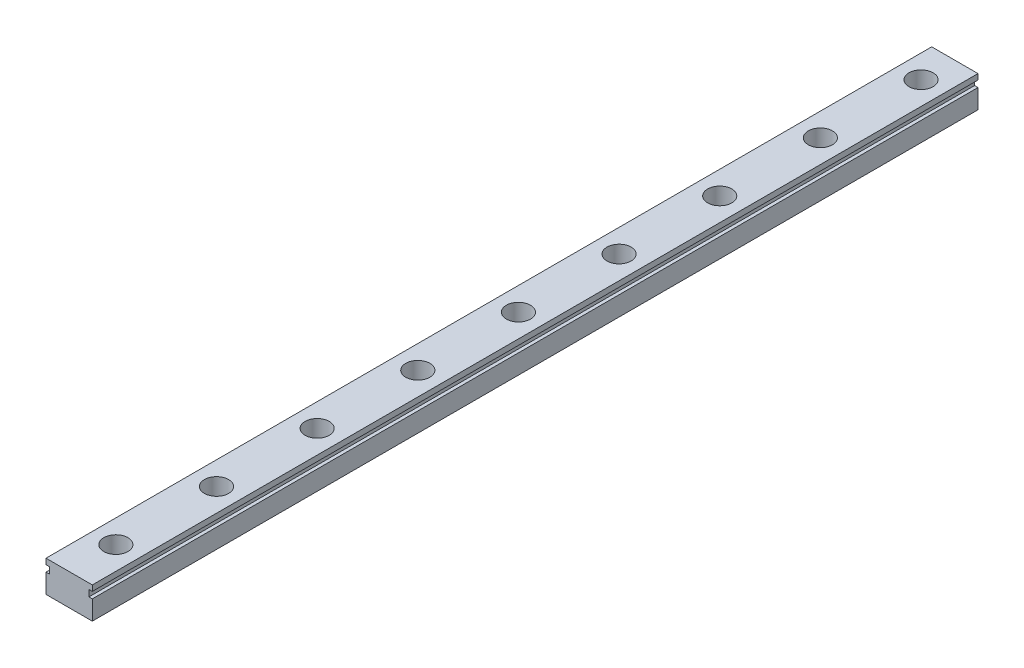
SolidWorks part; units mm, degrees
ref_plane "Front Plane" through (0, 0, 0) normal (0, 0, 1) x (1, 0, 0)
ref_plane "Top Plane" through (0, 0, 0) normal (0, 1, 0) x (1, 0, 0)
ref_plane "Right Plane" through (0, 0, 0) normal (1, 0, 0) x (0, 0, -1)
sketch "Sketch1" plane through (0, 0, 0) normal (0, 0, 1) x (1, 0, 0)
  line L1 (-5.75, -3.9) -> (5.75, -3.9)
  line L2 (-5.75, -3.9) -> (-5.75, 3.9)
  line L3 (-5.75, 3.9) -> (5.75, 3.9)
  line L4 (5.75, -3.9) -> (5.75, 3.9)
  line L5 (-5.75, -3.9) -> (5.75, 3.9) construction
  line L6 (-5.75, 3.9) -> (5.75, -3.9) construction
  point P0 (0, 0)
  dimension "D1" = 11.5
  dimension "D2" = 7.8
extrude "Boss-Extrude1" add sketch "Sketch1" along normal blind 220
sketch "Sketch2" plane through (0, 0, 220) normal (0, 0, 1) x (1, 0, 0)
  line L0 (5.75, -3.9) -> (5.75, 3.9) construction
  line L1 (5.75, 2.5) -> (4.9147, 2.5)
  line L2 (5.75, 2.5) -> (5.75, 0.9)
  line L3 (5.75, 0.9) -> (4.9147, 0.9)
  line L4 (4.9147, 2.5) -> (4.9147, 0.9)
  line L5 (5.75, 3.9) -> (-5.75, 3.9) construction
  line L7 (0, -55) -> (0, 55) construction
  line L8 (-5.75, 0.9) -> (-4.9147, 0.9)
  line L9 (-4.9147, 2.5) -> (-4.9147, 0.9)
  line L10 (-5.75, 2.5) -> (-4.9147, 2.5)
  line L11 (-5.75, 2.5) -> (-5.75, 0.9)
  dimension "D1" = 1.4
  dimension "D2" = 1.6
extrude "Cut-Extrude1" cut sketch "Sketch2" against normal through all
sketch "Sketch3" plane through (0, 3.9, 0) normal (0, 1, 0) x (1, 0, 0)
  line L0 (0, -223.2) -> (0, -215.9183) construction
  line L2 (5.75, -220) -> (-5.75, -220) construction
  circle A0 centre (0, -208.4) radius 3
  circle A1 centre (0, -183.4) radius 3
  circle A2 centre (0, -158.4) radius 3
  circle A3 centre (0, -133.4) radius 3
  circle A4 centre (0, -108.4) radius 3
  circle A5 centre (0, -83.4) radius 3
  circle A6 centre (0, -58.4) radius 3
  circle A7 centre (0, -33.4) radius 3
  circle A8 centre (0, -8.4) radius 3
  circle A9 centre (0, 16.6) radius 3
  circle A10 centre (0, 41.6) radius 3
  circle A11 centre (0, 66.6) radius 3
  circle A12 centre (0, 91.6) radius 3
  circle A13 centre (0, 116.6) radius 3
  circle A14 centre (0, 141.6) radius 3
  circle A15 centre (0, 166.6) radius 3
  circle A16 centre (0, 191.6) radius 3
  circle A17 centre (0, 216.6) radius 3
  circle A18 centre (0, 241.6) radius 3
  circle A19 centre (0, 266.6) radius 3
  circle A20 centre (0, 291.6) radius 3
  circle A21 centre (0, 316.6) radius 3
  circle A22 centre (0, 341.6) radius 3
  circle A23 centre (0, 366.6) radius 3
  circle A24 centre (0, 391.6) radius 3
  circle A25 centre (0, 416.6) radius 3
  circle A26 centre (0, 441.6) radius 3
  circle A27 centre (0, 466.6) radius 3
  circle A28 centre (0, 491.6) radius 3
  circle A29 centre (0, 516.6) radius 3
  dimension "D1" = 11.6
  dimension "D2" = 6
  dimension "D3" = 30
extrude "Cut-Extrude2" cut sketch "Sketch3" against normal blind 4.7
sketch "Sketch4" plane through (0, -0.8, 0) normal (0, 1, 0) x (1, 0, 0)
  circle A0 centre (0, -208.4) radius 1.7
  circle A1 centre (0, -183.4) radius 1.7
  circle A2 centre (0, -158.4) radius 1.7
  circle A3 centre (0, -133.4) radius 1.7
  circle A4 centre (0, -108.4) radius 1.7
  circle A5 centre (0, -83.4) radius 1.7
  circle A6 centre (0, -58.4) radius 1.7
  circle A7 centre (0, -33.4) radius 1.7
  circle A8 centre (0, -8.4) radius 1.7
  circle A9 centre (0, 16.6) radius 1.7
  circle A10 centre (0, 41.6) radius 1.7
  circle A11 centre (0, 66.6) radius 1.7
  circle A12 centre (0, 91.6) radius 1.7
  circle A13 centre (0, 116.6) radius 1.7
  circle A14 centre (0, 141.6) radius 1.7
  circle A15 centre (0, 166.6) radius 1.7
  circle A16 centre (0, 191.6) radius 1.7
  circle A17 centre (0, 216.6) radius 1.7
  circle A18 centre (0, 241.6) radius 1.7
  circle A19 centre (0, 266.6) radius 1.7
  circle A20 centre (0, 291.6) radius 1.7
  circle A21 centre (0, 316.6) radius 1.7
  circle A22 centre (0, 341.6) radius 1.7
  circle A23 centre (0, 366.6) radius 1.7
  circle A24 centre (0, 391.6) radius 1.7
  circle A25 centre (0, 416.6) radius 1.7
  circle A26 centre (0, 441.6) radius 1.7
  circle A27 centre (0, 466.6) radius 1.7
  circle A28 centre (0, 491.6) radius 1.7
  circle A29 centre (0, 516.6) radius 1.7
  dimension "D1" = 3.4
  dimension "D2" = 30
extrude "Cut-Extrude3" cut sketch "Sketch4" against normal through all
